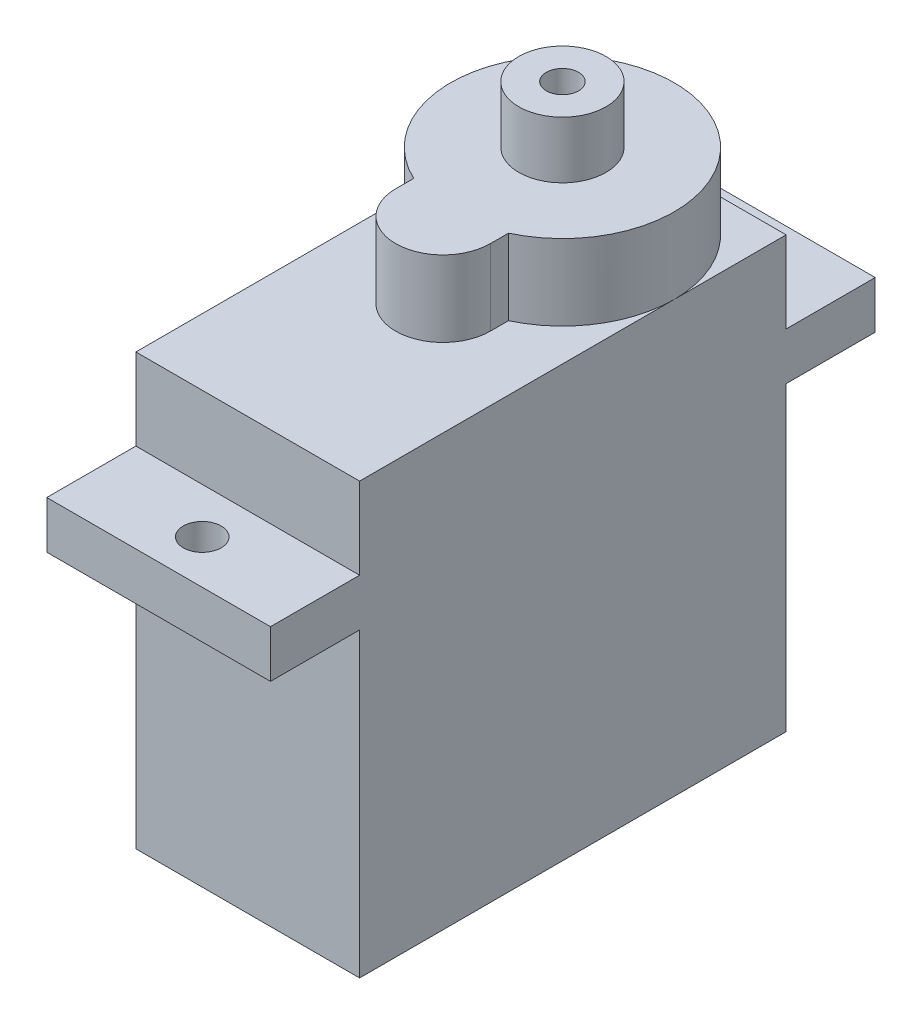
SolidWorks part; units mm, degrees
ref_plane "Front Plane" through (0, 0, 0) normal (0, 0, 1) x (1, 0, 0)
ref_plane "Top Plane" through (0, 0, 0) normal (0, 1, 0) x (1, 0, 0)
ref_plane "Right Plane" through (0, 0, 0) normal (1, 0, 0) x (0, 0, -1)
sketch "Sketch1" plane through (0, 0, 0) normal (0, 0, 1) x (1, 0, 0)
  line L0 (5.9, 0) -> (0, 0) construction
  line L1 (-5.9, 11.35) -> (5.9, 11.35)
  line L2 (-5.9, 11.35) -> (-5.9, -11.35)
  line L3 (-5.9, -11.35) -> (5.9, -11.35)
  line L4 (5.9, 11.35) -> (5.9, -11.35)
  line L5 (0, 0) -> (0, 11.35) construction
  dimension "D1" = 22.7
  dimension "D2" = 11.8
extrude "Boss-Extrude1" add sketch "Sketch1" along normal blind 22.5
sketch "Sketch2" plane through (0, 11.35, 0) normal (0, 1, 0) x (1, 0, 0)
  line L0 (0, 0) -> (0, -5.9) construction
  line L1 (0, -5.9) -> (5.9, -5.9) construction
  line L2 (2.5, -12.2) -> (2.5, -11.2442)
  line L3 (-2.5, -12.2) -> (-2.5, -11.2442)
  line L4 (0, -14.7) -> (0, -5.9) construction
  arc A0 (2.5, -11.2442) -> (-2.5, -11.2442) centre (0, -5.9) ccw
  arc A1 (-2.5, -12.2) -> (2.5, -12.2) centre (0, -12.2) ccw
  dimension "D1" = 11.8
  dimension "D2" = 5
  dimension "D3" = 8.8
extrude "Boss-Extrude2" add sketch "Sketch2" along normal blind 4
sketch "Sketch3" plane through (0, 15.35, 0) normal (0, 1, 0) x (1, 0, 0)
  circle A0 centre (0, -5.9) radius 2.3
  circle A1 centre (0, -5.9) radius 0.85
  dimension "D1" = 4.6
  dimension "D2" = 1.7
extrude "Boss-Extrude3" add sketch "Sketch3" along normal blind 3
sketch "Sketch4" plane through (-5.9, 0, 0) normal (-1, 0, 0) x (0, 0, 1)
  line L0 (-4.7, 7.05) -> (0, 7.05)
  line L1 (-4.7, 7.05) -> (27.2, 7.05) construction
  line L2 (-4.7, 7.05) -> (-4.7, 4.55)
  line L3 (-4.7, 4.55) -> (27.2, 4.55) construction
  line L4 (27.2, 7.05) -> (27.2, 4.55)
  line L5 (0, 11.35) -> (0, -11.35)
  line L6 (0, -11.35) -> (22.5, -11.35)
  line L7 (22.5, -11.35) -> (22.5, 11.35)
  line L8 (22.5, 11.35) -> (5.9, 11.35)
  line L9 (5.9, 11.35) -> (0, 11.35)
  line L10 (0, 11.35) -> (0, -11.35) construction
  line L11 (0, -11.35) -> (22.5, -11.35) construction
  line L12 (22.5, -11.35) -> (22.5, 11.35) construction
  line L13 (22.5, 11.35) -> (5.9, 11.35) construction
  line L14 (5.9, 11.35) -> (0, 11.35) construction
  line L15 (0, 7.05) -> (0, 4.55)
  line L16 (0, 4.55) -> (-4.7, 4.55)
  line L17 (27.2, 7.05) -> (22.5, 7.05)
  line L18 (22.5, 7.05) -> (22.5, 4.55)
  line L19 (22.5, 4.55) -> (27.2, 4.55)
  dimension "D2" = 2.5
  dimension "D3" = 4.7
  dimension "D4" = 4.7
  dimension "D5" = 15.9
  dimension "D1" = 0
extrude "Boss-Extrude4" add sketch "Sketch4" against normal up to surface (11.8 mm away) up to face at (5.9, 2.27, 10.18)
sketch "Sketch5" plane through (0, 7.05, 0) normal (0, 1, 0) x (1, 0, 0)
  line L0 (0, 4.7) -> (0, 0) construction
  line L1 (0, -27.2) -> (0, -22.5) construction
  line L4 (5.9, 0) -> (5.9, 4.7)
  line L5 (5.9, 4.7) -> (-5.9, 4.7)
  line L6 (-5.9, 4.7) -> (-5.9, 0)
  line L7 (-5.9, 0) -> (5.9, 0)
  line L8 (5.9, 0) -> (5.9, 4.7) construction
  line L9 (5.9, 4.7) -> (-5.9, 4.7) construction
  line L10 (-5.9, 4.7) -> (-5.9, 0) construction
  line L11 (-5.9, 0) -> (5.9, 0) construction
  line L13 (5.9, -27.2) -> (5.9, -22.5)
  line L14 (5.9, -22.5) -> (-5.9, -22.5)
  line L15 (-5.9, -22.5) -> (-5.9, -27.2)
  line L16 (-5.9, -27.2) -> (5.9, -27.2)
  line L17 (5.9, -27.2) -> (5.9, -22.5) construction
  line L18 (5.9, -22.5) -> (-5.9, -22.5) construction
  line L19 (-5.9, -22.5) -> (-5.9, -27.2) construction
  line L20 (-5.9, -27.2) -> (5.9, -27.2) construction
  circle A0 centre (0, 2.4) radius 1
  circle A1 centre (0, -24.9) radius 1
  dimension "D2" = 2
  dimension "D5" = 2
  dimension "D3" = 2.3
  dimension "D6" = 2.3
  dimension "D1" = 0
  dimension "D4" = 0
extrude "Cut-Extrude1" cut sketch "Sketch5" against normal up to next
